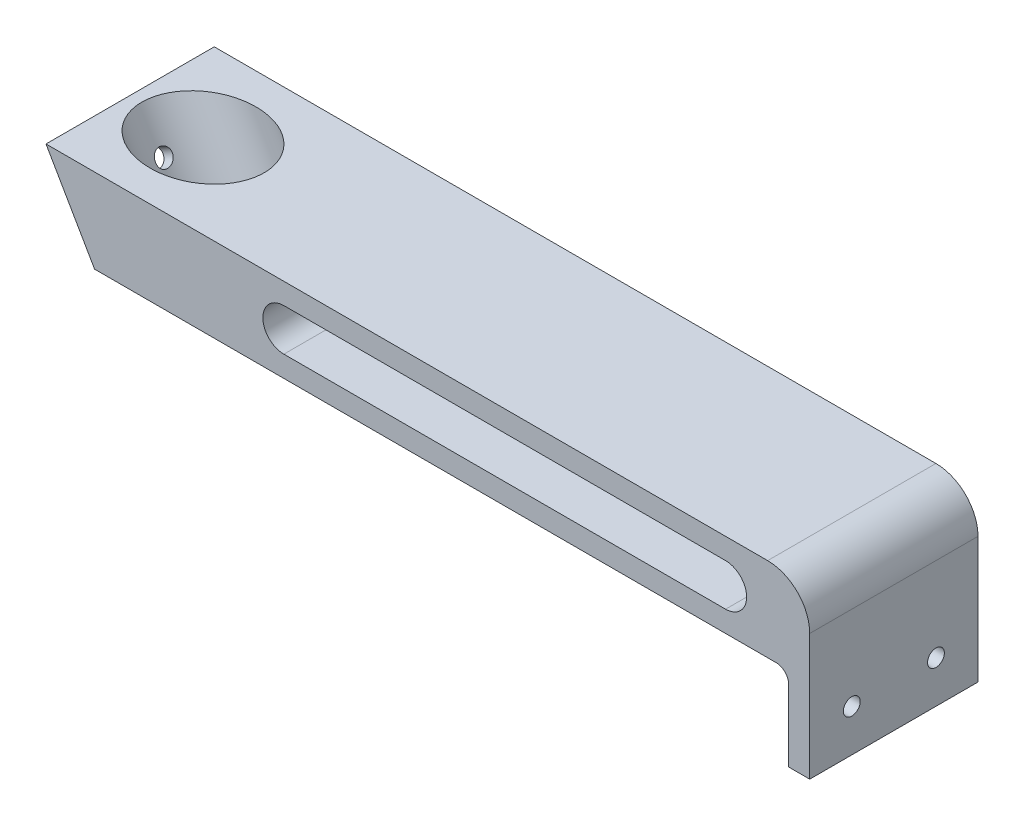
SolidWorks part; units mm, degrees
ref_plane "前视基准面" through (0, 0, 0) normal (0, 0, 1) x (1, 0, 0)
ref_plane "上视基准面" through (0, 0, 0) normal (0, 1, 0) x (1, 0, 0)
ref_plane "右视基准面" through (0, 0, 0) normal (1, 0, 0) x (0, 0, -1)
sketch "草图1" plane through (0, 0, 0) normal (0, 0, 1) x (1, 0, 0)
  line L0 (0, 0) -> (170, 0)
  line L1 (170, 0) -> (170, 20)
  line L2 (170, 20) -> (-11.547, 20)
  line L3 (-11.547, 20) -> (0, 0)
  line L4 (0, 0) -> (0, 151.1702) construction
  dimension "D1" = 30
  dimension "D2" = 20
  dimension "D3" = 170
extrude "凸台-拉伸1" add sketch "草图1" along normal blind 40
ref_plane "基准面1" through (-11.547, 20, 0) normal (-0.5, 0.866, 0) x (0, 0, -1)
sketch "草图2" plane through (-11.547, 20, 0) normal (-0.5, 0.866, 0) x (0, 0, -1)
  line L0 (0, 0) -> (-84.5846, 0) construction
  line L1 (0, -157.2243) -> (0, 0) construction
  circle A0 centre (-20, -15) radius 12.6
  point P5 (0, 0)
  dimension "D3" = 25.2
  dimension "D1" = 20
  dimension "D2" = 15
extrude "切除-拉伸1" cut sketch "草图2" against normal through all
sketch "草图3" plane through (0, 0, 0) normal (-0.866, -0.5, 0) x (0, 0, 1)
  line L0 (0, 0) -> (0, 49.6712) construction
  circle A0 centre (20, 11.4672) radius 2
  dimension "D2" = 4
  dimension "D1" = 40
extrude "切除-拉伸2" cut sketch "草图3" against normal up to next
sketch "草图4" plane through (0, 0, 0) normal (0, -1, 0) x (1, 0, 0)
  line L0 (0, 0) -> (170, 0) construction
  line L1 (170, 40) -> (165, 40)
  line L2 (170, 40) -> (170, 0)
  line L3 (170, 0) -> (165, 0)
  line L4 (165, 40) -> (165, 0)
  dimension "D1" = 5
extrude "凸台-拉伸2" add sketch "草图4" along normal blind 20
sketch "草图5" plane through (165, 0, 0) normal (-1, 0, 0) x (0, 0, 1)
  line L0 (20, 0) -> (20, -29.3991) construction
  line L1 (40, 0) -> (0, 0) construction
  line L2 (10, -10) -> (30, -10) construction
  circle A0 centre (10, -10) radius 2
  circle A1 centre (30, -10) radius 2
  dimension "D1" = 20
  dimension "D3" = 4
  dimension "D2" = 10
extrude "切除-拉伸3" cut sketch "草图5" against normal through all
fillet "圆角1" radius 10 1 edges at (170, 20, 20)
fillet "圆角2" radius 3 1 edges at (165, 0, 20)
sketch "草图6" plane through (0, 0, 0) normal (0, 0, -1) x (-1, 0, 0)
  line L0 (-150, 10) -> (-45, 10) construction
  line L1 (-150, 15) -> (-45, 15)
  line L2 (-150, 5) -> (-45, 5)
  line L3 (-160, 20) -> (11.547, 20) construction
  line L4 (-165, -20) -> (-165, -3) construction
  line L5 (0, 0) -> (0, 35.4113) construction
  arc A0 (-150, 15) -> (-150, 5) centre (-150, 10) ccw
  arc A1 (-45, 5) -> (-45, 15) centre (-45, 10) ccw
  point P2 (-97.5, 10)
  dimension "D1" = 10
  dimension "D2" = 5
  dimension "D3" = 15
  dimension "D4" = 45
extrude "切除-拉伸4" cut sketch "草图6" against normal through all
